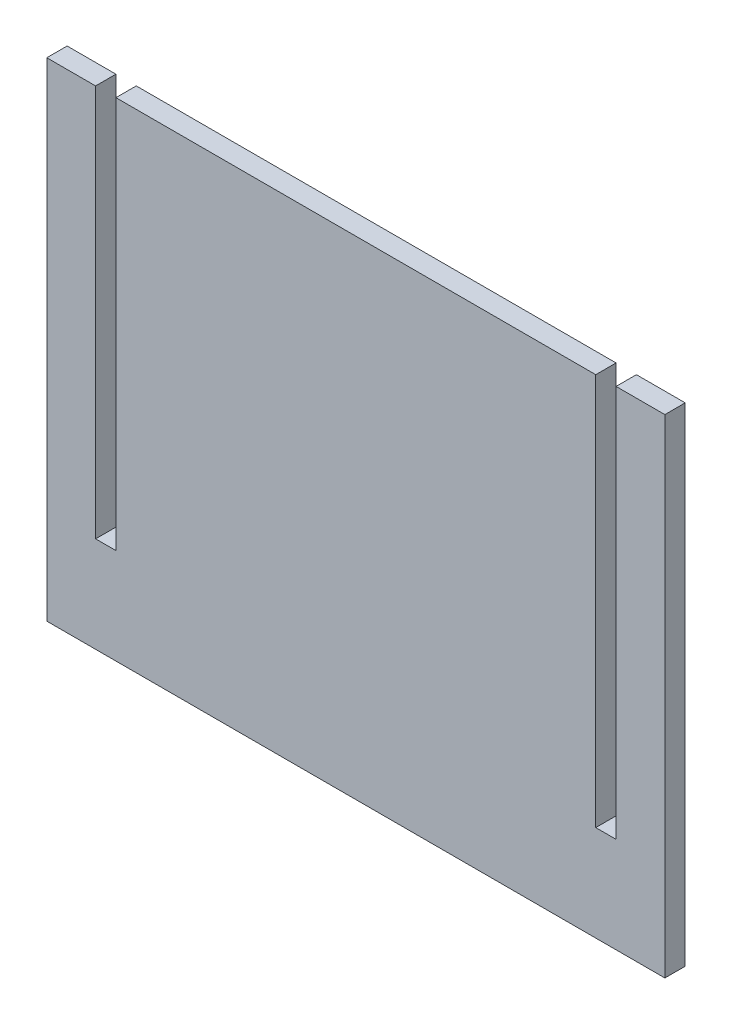
SolidWorks part; units mm, degrees
ref_plane "Front Plane" through (0, 0, 0) normal (0, 0, 1) x (1, 0, 0)
ref_plane "Top Plane" through (0, 0, 0) normal (0, 1, 0) x (1, 0, 0)
ref_plane "Right Plane" through (0, 0, 0) normal (1, 0, 0) x (0, 0, -1)
sketch "Sketch1" plane through (0, 0, 0) normal (0, 0, 1) x (1, 0, 0)
  line L0 (48.26, 76.2) -> (48.26, 0) construction
  line L1 (0, 0) -> (96.52, 0)
  line L2 (0, 0) -> (0, 76.2)
  line L3 (0, 76.2) -> (96.52, 76.2)
  line L4 (96.52, 0) -> (96.52, 76.2)
  line L5 (7.62, 76.2) -> (10.795, 76.2)
  line L6 (7.62, 76.2) -> (7.62, 14.9428)
  line L7 (7.62, 14.9428) -> (10.795, 14.9428)
  line L8 (10.795, 76.2) -> (10.795, 14.9428)
  line L9 (88.9, 14.9428) -> (85.725, 14.9428)
  line L10 (85.725, 76.2) -> (85.725, 14.9428)
  line L11 (88.9, 76.2) -> (88.9, 14.9428)
  dimension "D1" = 96.52
  dimension "D2" = 76.2
  dimension "D3" = 7.62
  dimension "D4" = 3.175
extrude "Boss-Extrude1" add sketch "Sketch1" along normal blind 3.175 contours L0 L3 L8 L7 L6 L2 L1 | L3 L0 L1 L4 L11 L9 L10
